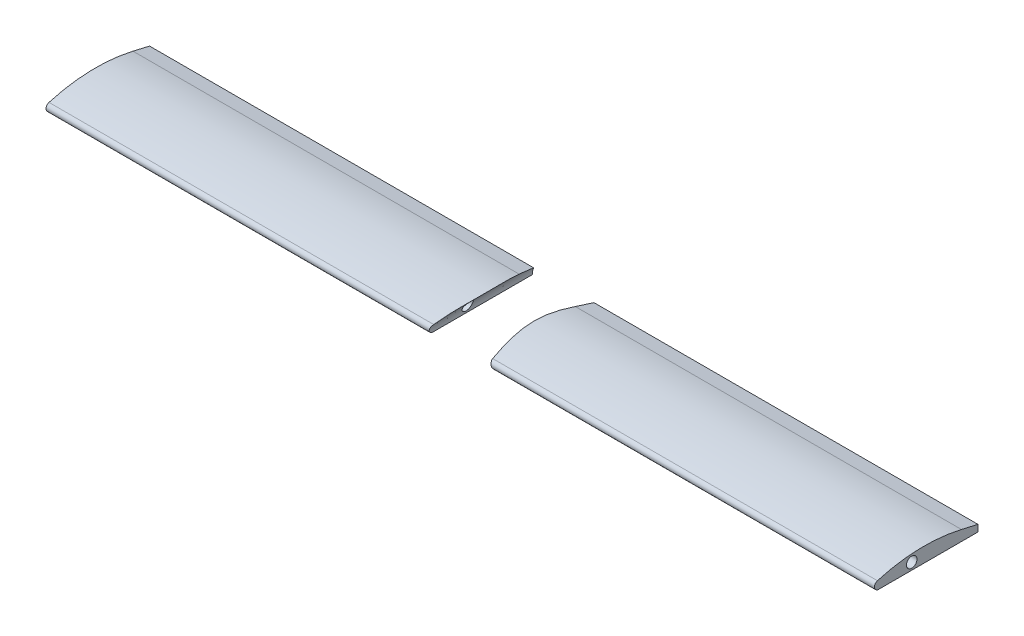
SolidWorks part; units mm, degrees
material "Acrylic (Medium-high impact)"
ref_plane "Front Plane" through (0, 0, 0) normal (0, 0, 1) x (1, 0, 0)
ref_plane "Top Plane" through (0, 0, 0) normal (0, 1, 0) x (1, 0, 0)
ref_plane "Right Plane" through (0, 0, 0) normal (1, 0, 0) x (0, 0, -1)
sketch "Sketch1" plane through (0, 0, 0) normal (1, 0, 0) x (0, 0, -1)
  line L0 (0, 0) -> (120, 0)
  line L1 (120, 0) -> (120, 8)
  line L2 (120, 8) -> (100, 12.6475)
  arc A0 (100, 12.6475) -> (-1.4034, 9.799) centre (54.7307, -182.1618) ccw
  arc A1 (0, 0) -> (-1.4034, 9.799) centre (0, 5) cw
  circle A2 centre (40.0505, 8.5) radius 6.35
  point P8 (-99.933, 45.9668)
  point P9 (-4.9495, 4.2912)
  point P10 (114.534, 9.7868)
  point P11 (101.5443, 12.4178)
  dimension "D1" = 12.7
  dimension "D5" = 5
  dimension "D6" = 200
  dimension "D2" = 8
  dimension "D3" = 120
  dimension "D4" = 45
  dimension "D7" = 8.5
  dimension "D8" = 20
extrude "Boss-Extrude1" add sketch "Sketch1" along normal mid plane 1000
sketch "Sketch2" plane through (0, 0, 0) normal (0, 0, 1) x (1, 0, 0)
  line L0 (500, 0) -> (-500, 0) construction
  ellipse E0 centre (0, 0) end of major axis (-38, 0) minor radius 28
  dimension "D1" = 28
  dimension "D2" = 38
extrude "Cut-Extrude1" cut sketch "Sketch2" against normal through all both and the other way through all
